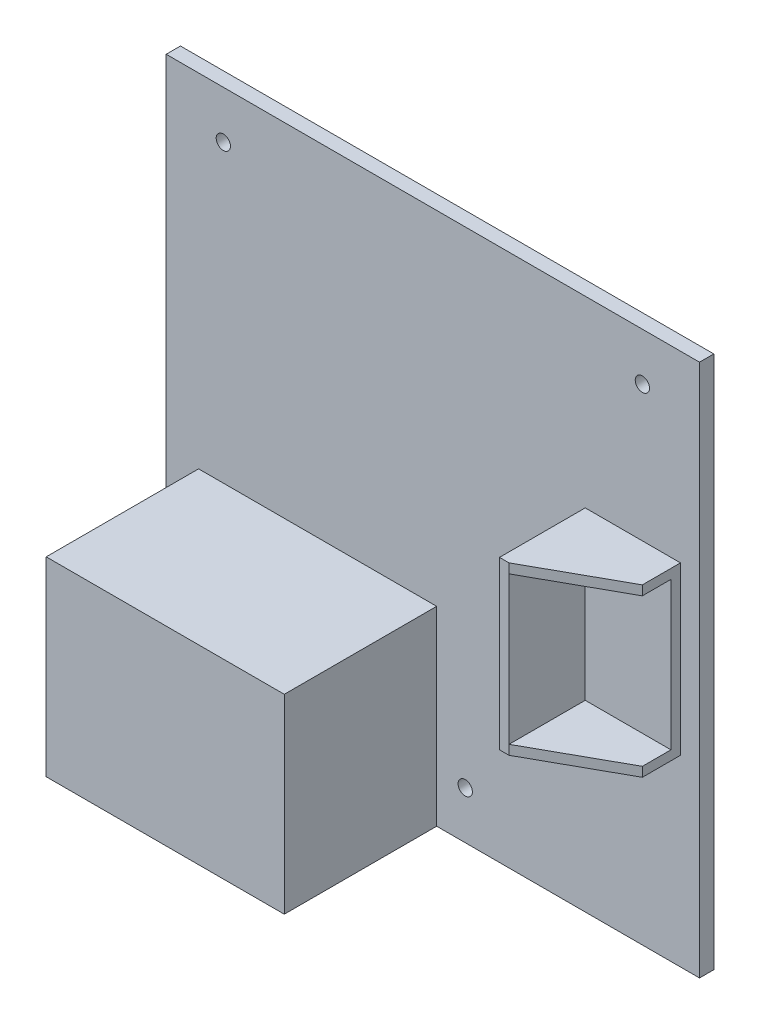
SolidWorks part; units mm, degrees
ref_plane "Front" through (0, 0, 0) normal (0, 0, 1) x (1, 0, 0)
ref_plane "Top" through (0, 0, 0) normal (0, 1, 0) x (1, 0, 0)
ref_plane "Right" through (0, 0, 0) normal (1, 0, 0) x (0, 0, -1)
sketch "Sketch1" plane through (0, 0, 0) normal (0, 0, 1) x (1, 0, 0)
  line L1 (-56, -56) -> (56, -56)
  line L2 (-56, -56) -> (-56, 56)
  line L3 (-56, 56) -> (56, 56)
  line L4 (56, -56) -> (56, 56)
  line L5 (-56, -56) -> (56, 56) construction
  line L6 (-56, 56) -> (56, -56) construction
  point P0 (0, 0)
  dimension "D1" = 112
extrude "Boss-Extrude1" add sketch "Sketch1" along normal blind 3
sketch "Sketch2" plane through (0, 0, 3) normal (0, 0, 1) x (1, 0, 0)
  line L0 (-56, -56) -> (56, -56) construction
  line L1 (-49.1968, -56) -> (0.8032, -56)
  line L2 (-49.1968, -56) -> (-49.1968, -16)
  line L3 (-49.1968, -16) -> (0.8032, -16)
  line L4 (0.8032, -56) -> (0.8032, -16)
  line L5 (-49.1968, -56) -> (0.8032, -16) construction
  line L6 (-49.1968, -16) -> (0.8032, -56) construction
  point P4 (-24.1968, -36)
  dimension "D1" = 40
  dimension "D2" = 50
extrude "Boss-Extrude2" add sketch "Sketch2" along normal blind 32
sketch "Sketch3" plane through (0, 0, 3) normal (0, 0, 1) x (1, 0, 0)
  line L0 (56, 56) -> (-56, 56) construction
  line L1 (-56, 56) -> (-56, -56) construction
  line L2 (56, -56) -> (56, 56) construction
  line L3 (0.8032, -56) -> (56, -56) construction
  line L4 (0.8032, -56) -> (0.8032, -16) construction
  circle A0 centre (-44, 46) radius 1.5
  circle A1 centre (44, 46) radius 1.5
  circle A2 centre (6.8032, -46) radius 1.5
  dimension "D1" = 3
  dimension "D2" = 3
  dimension "D3" = 10
  dimension "D4" = 12
  dimension "D5" = 12
  dimension "D6" = 3
  dimension "D7" = 10
  dimension "D8" = 6
extrude "Cut-Extrude1" cut sketch "Sketch3" against normal up to next
sketch "Sketch4" plane through (0, 0, 3) normal (0, 0, 1) x (1, 0, 0)
  line L0 (56, -56) -> (56, 56) construction
  line L1 (32, -17.5) -> (52, -17.5)
  line L2 (32, -17.5) -> (32, 17.5)
  line L3 (32, 17.5) -> (52, 17.5)
  line L4 (52, -17.5) -> (52, 17.5)
  line L5 (32, -17.5) -> (52, 17.5) construction
  line L6 (32, 17.5) -> (52, -17.5) construction
  point P0 (42, 0)
  point P5 (0, 0)
  dimension "D1" = 35
  dimension "D2" = 20
  dimension "D3" = 4
extrude "Boss-Extrude3" add sketch "Sketch4" along normal blind 18
sketch "Sketch5" plane through (0, 0, 21) normal (0, 0, 1) x (1, 0, 0)
  line L0 (52, 15.5) -> (34, 15.5)
  line L1 (34, 15.5) -> (34, -15.5)
  line L2 (34, -15.5) -> (52, -15.5)
  line L4 (52, -17.5) -> (52, 17.5)
  line L5 (52, 17.5) -> (32, 17.5)
  line L6 (32, 17.5) -> (32, -17.5)
  line L7 (32, -17.5) -> (52, -17.5)
  line L8 (52, -17.5) -> (52, 17.5)
  line L9 (52, 17.5) -> (32, 17.5)
  line L10 (32, 17.5) -> (32, -17.5)
  line L11 (32, -17.5) -> (52, -17.5)
  line L12 (50, 15.5) -> (34, 15.5) construction
  line L13 (34, -15.5) -> (50, -15.5) construction
  line L14 (50, -15.5) -> (50, 15.5) construction
  line M9 (52, -17.5) -> (52, 17.5)
  dimension "D1" = 0
  dimension "D2" = 2
extrude "Cut-Extrude2" cut sketch "Sketch5" against normal blind 16 contours L1 L2 L0 M9
sketch "Sketch6" plane through (0, 17.5, 0) normal (0, 1, 0) x (1, 0, 0)
  line L0 (34, -21) -> (52, -11)
  line L1 (52, -21) -> (32, -21) construction
  line L2 (52, -21) -> (52, -3) construction
  line L3 (34, -21) -> (52, -21)
  line L4 (52, -21) -> (52, -11)
  dimension "D1" = 8
  dimension "D2" = 2
extrude "Cut-Extrude3" cut sketch "Sketch6" against normal through all
